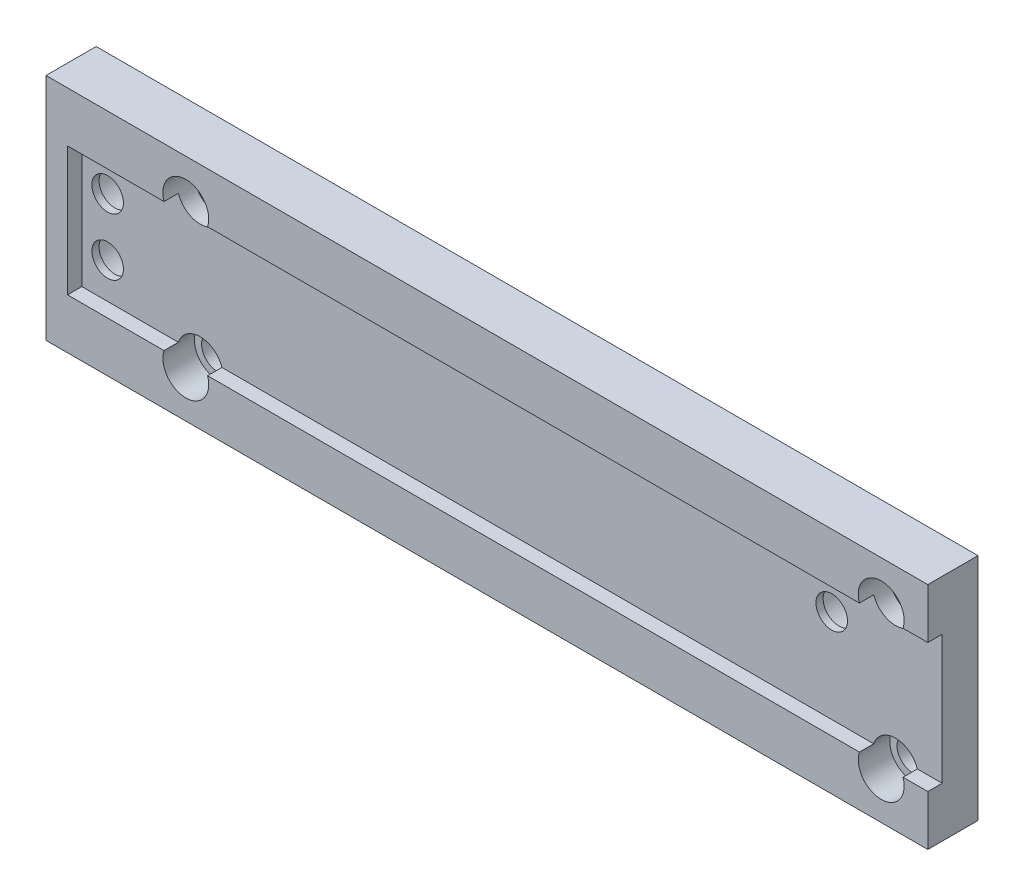
SolidWorks part; units mm, degrees
other "Markup1"
sketch "Sketch9" plane through (30.75, -7, 3.5) normal (0.2192, -0.3504, 0.9106) x (0.9742, 0.0271, -0.2241)
ref_plane "Front Plane" through (0, 0, 0) normal (0, 0, 1) x (1, 0, 0)
ref_plane "Top Plane" through (0, 0, 0) normal (0, 1, 0) x (1, 0, 0)
ref_plane "Right Plane" through (0, 0, 0) normal (1, 0, 0) x (0, 0, -1)
sketch "Sketch1" plane through (0, 0, 0) normal (0, 0, 1) x (1, 0, 0)
  line L1 (-30.75, 8) -> (30.75, 8)
  line L2 (-30.75, 8) -> (-30.75, -8)
  line L3 (-30.75, -8) -> (30.75, -8)
  line L4 (30.75, 8) -> (30.75, -8)
  line L5 (-30.75, 8) -> (30.75, -8) construction
  line L6 (-30.75, -8) -> (30.75, 8) construction
  point P0 (0, 0)
  dimension "D1" = 16
  dimension "D2" = 61.5
extrude "Boss-Extrude1" add sketch "Sketch1" along normal blind 3.5
sketch "Sketch5" plane through (0, 0, 3.5) normal (0, 0, 1) x (1, 0, 0)
  line L1 (-29.25, 4.5) -> (30.75, 4.5)
  line L2 (-29.25, 4.5) -> (-29.25, -4.5)
  line L3 (-29.25, -4.5) -> (30.75, -4.5)
  line L4 (30.75, 4.5) -> (30.75, -4.5)
  line L5 (-29.25, 4.5) -> (30.75, -4.5) construction
  line L6 (-29.25, -4.5) -> (30.75, 4.5) construction
  line L9 (-30.75, 8) -> (-30.75, -8) construction
  line L10 (30.75, -8) -> (30.75, 8) construction
  point P0 (0.75, 0)
  point P10 (0, 0)
  dimension "D1" = 9
  dimension "D2" = 1.5
extrude "Cut-Extrude3" cut sketch "Sketch5" against normal blind 1
sketch "Sketch6" plane through (0, 0, 2.5) normal (0, 0, 1) x (1, 0, 0)
  line L0 (-18.7435, 0) -> (18.5554, 0) construction
  line L1 (30.75, -8) -> (30.75, -4.5) construction
  circle A0 centre (-27.45, 2) radius 1.1
  circle A1 centre (-27.45, -2) radius 1.1
  circle A2 centre (23.05, 2) radius 1.1
  dimension "D1" = 7.7
  dimension "D2" = 2.2
  dimension "D3" = 50.5
  dimension "D4" = 2
extrude "Cut-Extrude4" cut sketch "Sketch6" against normal through all
sketch "Sketch7" plane through (0, 0, 3.5) normal (0, 0, 1) x (1, 0, 0)
  line L0 (30.75, -4.5) -> (30.75, 4.5) construction
  line L1 (-21, 5) -> (27.5, 5) construction
  line L2 (-21, 5) -> (-21, -5) construction
  line L3 (-21, -5) -> (27.5, -5) construction
  line L4 (27.5, 5) -> (27.5, -5) construction
  line L5 (-21, 5) -> (27.5, -5) construction
  line L6 (-21, -5) -> (27.5, 5) construction
  circle A0 centre (-21, 5) radius 1.6
  circle A1 centre (-21, -5) radius 1.6
  circle A2 centre (27.5, 5) radius 1.6
  circle A3 centre (27.5, -5) radius 1.6
  point P0 (3.25, 0)
  dimension "D3" = 3.2
  dimension "D1" = 48.5
  dimension "D2" = 10
  dimension "D4" = 27.5
extrude "Cut-Extrude5" cut sketch "Sketch7" against normal blind 2.2
sketch "Sketch8" plane through (0, 0, 2.5) normal (0, 0, 1) x (1, 0, 0)
  circle A0 centre (-21, 5) radius 1.1
  circle A1 centre (-21, -5) radius 1.1
  circle A2 centre (27.5, 5) radius 1.1
  circle A3 centre (27.5, -5) radius 1.1
  dimension "D1" = 2.2
extrude "Cut-Extrude6" cut sketch "Sketch8" against normal through all
sketch "Sketch11" plane through (0, 0, 0) normal (0, 0, -1) x (-1, 0, 0)
  circle A0 centre (-23.05, 2) radius 1.95
  circle A1 centre (27.45, -2) radius 1.95
  circle A2 centre (27.45, 2) radius 1.95
  dimension "D1" = 3.9
extrude "Cut-Extrude10" cut sketch "Sketch11" against normal blind 2
